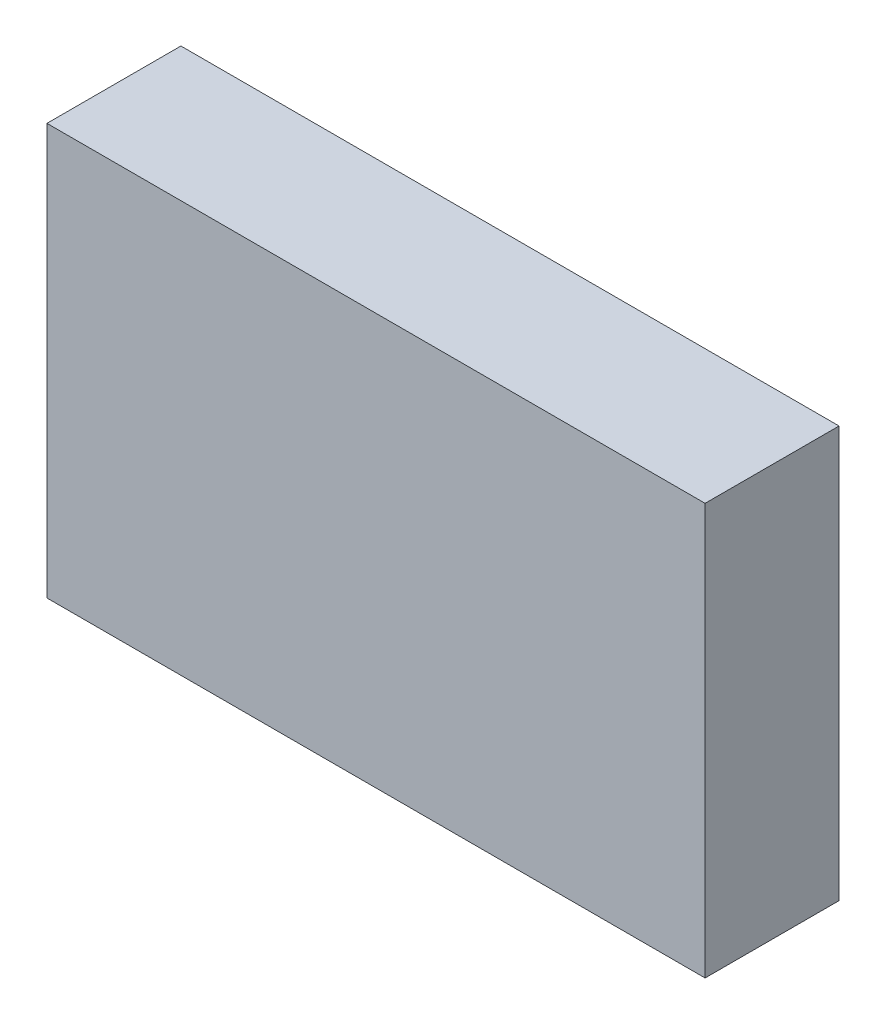
SolidWorks part; units mm, degrees
ref_plane "Ön Düzlem" through (0, 0, 0) normal (0, 0, 1) x (1, 0, 0)
ref_plane "Üst Düzlem" through (0, 0, 0) normal (0, 1, 0) x (1, 0, 0)
ref_plane "Sağ Düzlem" through (0, 0, 0) normal (1, 0, 0) x (0, 0, -1)
sketch "Sketch1" plane through (0, 0, 0) normal (0, 0, 1) x (1, 0, 0)
  line L1 (-74.7828, 29.1421) -> (38.2213, 29.1421)
  line L2 (-74.7828, 29.1421) -> (-74.7828, -41.4408)
  line L3 (-74.7828, -41.4408) -> (38.2213, -41.4408)
  line L4 (38.2213, 29.1421) -> (38.2213, -41.4408)
extrude "Extrude1" add sketch "Sketch1" along normal blind 23
